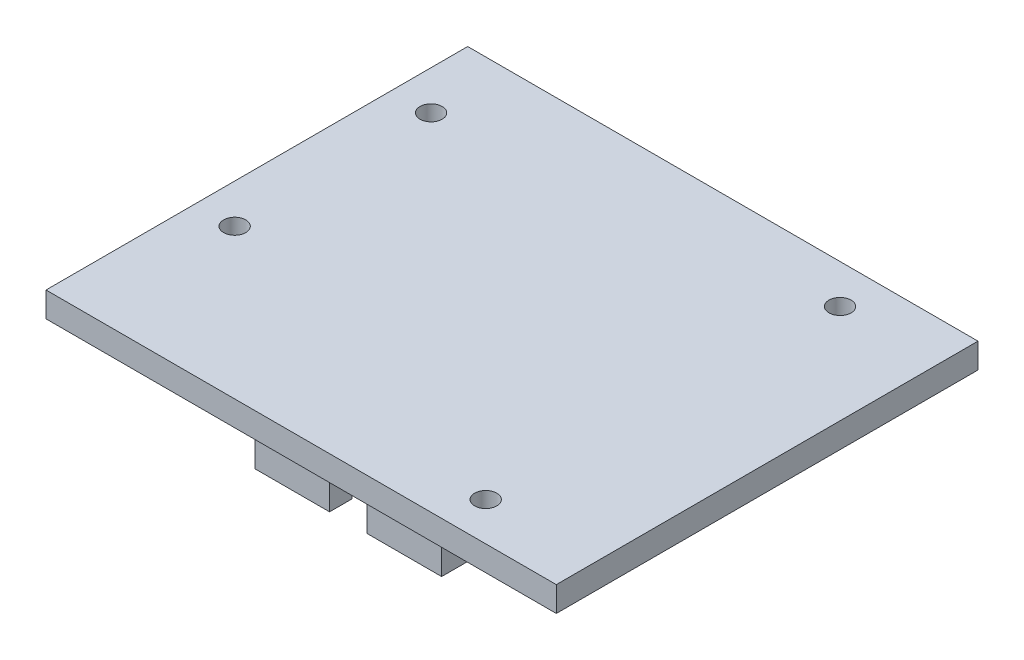
SolidWorks part; units mm, degrees
ref_plane "前基準面" through (0, 0, 0) normal (0, 0, 1) x (1, 0, 0)
ref_plane "上基準面" through (0, 0, 0) normal (0, 1, 0) x (1, 0, 0)
ref_plane "右基準面" through (0, 0, 0) normal (1, 0, 0) x (0, 0, -1)
sketch "草圖1" plane through (0, 0, 0) normal (0, 1, 0) x (1, 0, 0)
  line L0 (35.7, -24.6262) -> (22.6, -24.6262) construction
  line L1 (35.7, -29.5) -> (-35.7, -29.5)
  line L2 (35.7, -29.5) -> (35.7, 29.5)
  line L3 (35.7, 29.5) -> (-35.7, 29.5)
  line L4 (-35.7, -29.5) -> (-35.7, 29.5)
  line L5 (0, 29.5) -> (0, -29.5) construction
  line L6 (35.7, 0) -> (-35.7, 0) construction
  line L7 (17.7096, -29.5) -> (17.7096, -25.97) construction
  point P0 (0, 0)
  dimension "D1" = 59
  dimension "D2" = 71.4
extrude "填料-伸長1" add sketch "草圖1" against normal blind 3.5
sketch "草圖2" plane through (0, 0, 0) normal (0, 1, 0) x (1, 0, 0)
  line L0 (35.7, -24.1305) -> (22, -24.1305) construction
  line L1 (35.7, -29.5) -> (35.7, 29.5) construction
  line L2 (20.4534, -29.5) -> (20.4534, -25.6) construction
  line L3 (-35.7, -29.5) -> (35.7, -29.5) construction
  line L4 (-30.2236, 29.5) -> (-30.2236, 20.3) construction
  line L5 (-30.3149, -29.5) -> (-30.3149, -10) construction
  line L6 (35.7, 29.5) -> (-35.7, 29.5) construction
  line L7 (-35.7, -8.578) -> (-31.7, -8.578) construction
  line L8 (-35.7, 29.5) -> (-35.7, -29.5) construction
  line L9 (-35.7, -29.5) -> (35.7, -29.5) construction
  line L10 (35.7, 24.1305) -> (23.2, 24.1305) construction
  line L11 (35.7, -29.5) -> (35.7, 29.5) construction
  line L12 (21.9144, 29.5) -> (21.9144, 25.44) construction
  circle A0 centre (20.4534, -24.1305) radius 1.55
  circle A1 centre (-30.2236, 18.9) radius 1.55
  circle A2 centre (-30.2236, -8.578) radius 1.55
  circle A3 centre (21.85, 24.05) radius 1.55
  dimension "D1" = 3.1
  dimension "D2" = 3.1
  dimension "D3" = 3.1
  dimension "D4" = 3.1
extrude "除料-伸長4" cut sketch "草圖2" along normal blind 8.5 and the other way blind 15
sketch "草圖5" plane through (0, -3.5, 0) normal (0, -1, 0) x (-1, 0, 0)
  line L1 (-13.055, 22.9) -> (13.055, 22.9)
  line L2 (-13.055, 22.9) -> (-13.055, -22.9)
  line L3 (-13.055, -22.9) -> (13.055, -22.9)
  line L4 (13.055, 22.9) -> (13.055, -22.9)
  line L5 (0, -22.9) -> (0, 22.9) construction
  line L6 (-13.055, 0) -> (13.055, 0) construction
  point P0 (0, 0)
  dimension "D1" = 26.11
  dimension "D2" = 45.8
extrude "填料-伸長2" add sketch "草圖5" along normal blind 10.15
sketch "草圖6" plane through (0, -13.65, 0) normal (0, -1, 0) x (1, 0, 0)
  line L1 (10, -19.775) -> (-10, -19.775)
  line L2 (10, -19.775) -> (10, 19.775)
  line L3 (10, 19.775) -> (-10, 19.775)
  line L4 (-10, -19.775) -> (-10, 19.775)
  line L5 (0, 19.775) -> (0, -19.775) construction
  line L6 (10, 0) -> (-10, 0) construction
  point P0 (0, 0)
  dimension "D1" = 39.55
  dimension "D2" = 20
extrude "除料-伸長5" cut sketch "草圖6" against normal blind 10.15
sketch "草圖9" plane through (0, 0, 22.9) normal (0, 0, 1) x (1, 0, 0)
  line L0 (0, -1003.5) -> (0, 48996.5) construction
  line L1 (13.055, -3.5) -> (-13.055, -3.5) construction
  line L2 (-1013.055, -8.575) -> (48986.945, -8.575) construction
  line L3 (-13.055, -13.65) -> (-13.055, -3.5) construction
  line L4 (13.055, -13.65) -> (-13.055, -13.65) construction
  line L5 (-2.525, -3.5) -> (2.525, -3.5)
  line L6 (-2.525, -3.5) -> (-2.525, -13.65)
  line L7 (-2.525, -13.65) -> (2.525, -13.65)
  line L8 (2.525, -3.5) -> (2.525, -13.65)
  line L9 (-2.525, -3.5) -> (2.525, -13.65) construction
  line L10 (-2.525, -13.65) -> (2.525, -3.5) construction
  point P5 (0, -3.5)
  point P6 (0, -8.575)
  point P10 (-13.055, -8.575)
  dimension "D1" = 5.05
extrude "除料-伸長6" cut sketch "草圖9" against normal blind 10
sketch "草圖12" plane through (0, -13.65, 0) normal (0, -1, 0) x (1, 0, 0)
  line L0 (-2.525, 19.775) -> (-10, 19.775) construction
  line L1 (-2.525, 22.9) -> (-2.625, 22.9)
  line L2 (-2.525, 22.9) -> (-2.525, 19.775)
  line L3 (-2.525, 19.775) -> (-2.625, 19.775)
  line L4 (-2.625, 22.9) -> (-2.625, 19.775)
  line L5 (10, 19.775) -> (2.525, 19.775) construction
  line L6 (2.525, 22.9) -> (2.625, 22.9)
  line L7 (2.525, 22.9) -> (2.525, 19.775)
  line L8 (2.525, 19.775) -> (2.625, 19.775)
  line L9 (2.625, 22.9) -> (2.625, 19.775)
  dimension "D1" = 0.1
  dimension "D2" = 0.1
extrude "除料-伸長7" cut sketch "草圖12" against normal blind 10
